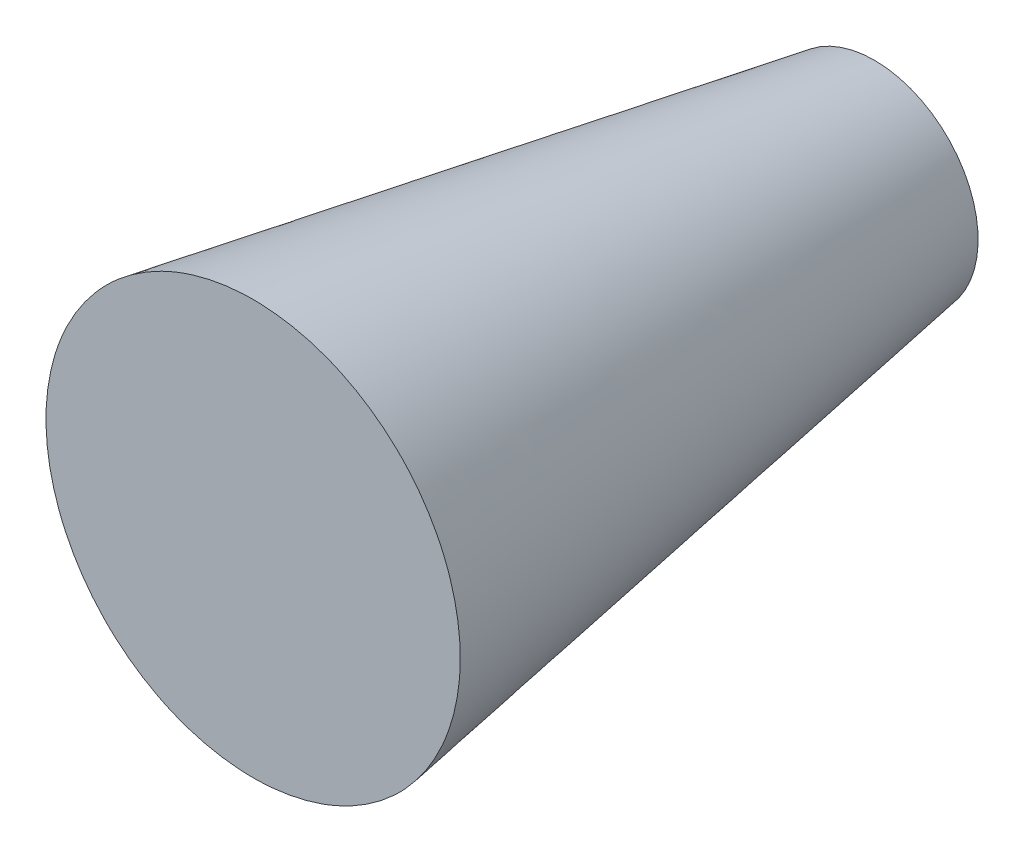
SolidWorks part; units mm, degrees
ref_plane "前视基准面" through (0, 0, 0) normal (0, 0, 1) x (1, 0, 0)
ref_plane "上视基准面" through (0, 0, 0) normal (0, 1, 0) x (1, 0, 0)
ref_plane "右视基准面" through (0, 0, 0) normal (1, 0, 0) x (0, 0, -1)
other "Configuration Table"
sketch "Profile1" plane through (0, 0, 0) normal (0, 0, 1) x (1, 0, 0)
  circle A0 centre (0, 0) radius 5
  point P2 (5, 0)
ref_plane "Plane1" through (0, 0, 15) normal (0, 0, 1) x (1, 0, 0)
sketch "Profile2" plane through (0, 0, 15) normal (0, 0, 1) x (1, 0, 0)
  circle A0 centre (0, 0) radius 7.5
  point P2 (-3.75, 6.4952)
ref_plane "Plane2" through (0, 0, 30) normal (0, 0, 1) x (1, 0, 0)
sketch "Profile3" plane through (0, 0, 30) normal (0, 0, 1) x (1, 0, 0)
  circle A0 centre (0, 0) radius 10
  point P2 (-5, -8.6603)
loft "modern_loft_pick_points3" add profiles "Profile1", "Profile2", "Profile3"
